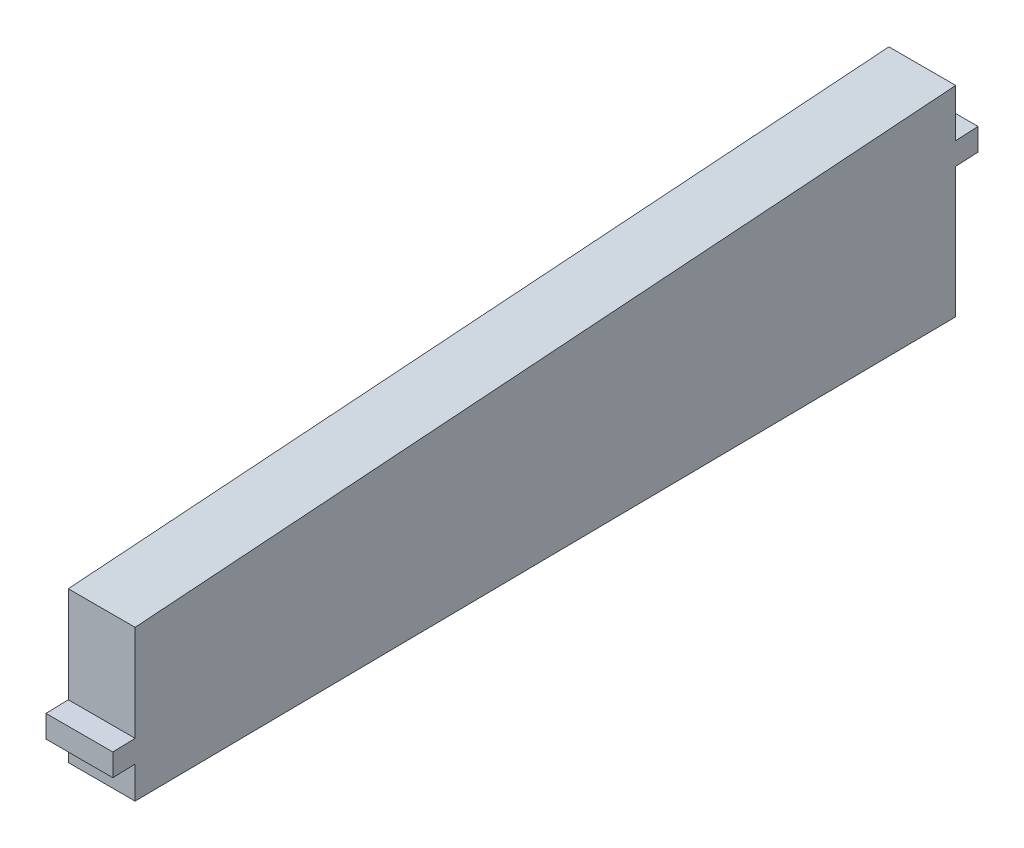
SolidWorks part; units mm, degrees
material "Balsa"
ref_plane "Front Plane" through (0, 0, 0) normal (0, 0, 1) x (1, 0, 0)
ref_plane "Top Plane" through (0, 0, 0) normal (0, 1, 0) x (1, 0, 0)
ref_plane "Right Plane" through (0, 0, 0) normal (1, 0, 0) x (0, 0, -1)
sketch "Sketch1" plane through (243.0177, 0, 0) normal (1, 0, 0) x (0, 0, -1)
  line L1 (-1380.6604, 359.6586) -> (-1377.4854, 359.7549) construction
  line L2 (-1380.6604, 362.8336) -> (-1380.6604, 359.6586)
  line L3 (-1377.4854, 362.9299) -> (-1380.6604, 362.8336) construction
  line L5 (-1260.5395, 375.0497) -> (-1257.3645, 375.2173) construction
  line L6 (-1257.3645, 375.2173) -> (-1257.3645, 378.3923) construction
  line L7 (-1257.3645, 378.3923) -> (-1260.5395, 378.2247) construction
  line L8 (-1377.4854, 376.6305) -> (-1380.6604, 376.4022) construction
  line L9 (-1377.4854, 355.1762) -> (-1380.6604, 355.1406) construction
  line L10 (-1257.3645, 356.5206) -> (-1260.5395, 356.4851) construction
  line L11 (-1257.3645, 385.2665) -> (-1260.5395, 385.0382) construction
  line L13 (-1380.6604, 359.6586) -> (-1377.4854, 359.7549)
  line L15 (-1377.4854, 362.9299) -> (-1380.6604, 362.8336)
  line L17 (-1260.5395, 375.0497) -> (-1257.3645, 375.2173)
  line L18 (-1257.3645, 375.2173) -> (-1257.3645, 378.3923)
  line L19 (-1257.3645, 378.3923) -> (-1260.5395, 378.2247)
  line L20 (-1377.4854, 376.6305) -> (-1380.6604, 376.4022) construction
  line L21 (-1377.4854, 355.1762) -> (-1380.6604, 355.1406) construction
  line L22 (-1257.3645, 356.5206) -> (-1260.5395, 356.4851) construction
  line L23 (-1257.3645, 385.2665) -> (-1260.5395, 385.0382) construction
  line L24 (-1377.4854, 376.6305) -> (-1377.4854, 362.9299)
  line L25 (-1377.4854, 355.1762) -> (-1377.4854, 359.7549)
  line L26 (-1377.4854, 355.1762) -> (-1260.5395, 356.4851)
  line L27 (-1260.5395, 356.4851) -> (-1260.5395, 375.0497)
  line L28 (-1260.5395, 378.2247) -> (-1260.5395, 385.0382)
  line L29 (-1260.5395, 385.0382) -> (-1377.4854, 376.6305)
extrude "Boss-Extrude1" add sketch "Sketch1" along normal up to surface (9.525 mm away)
